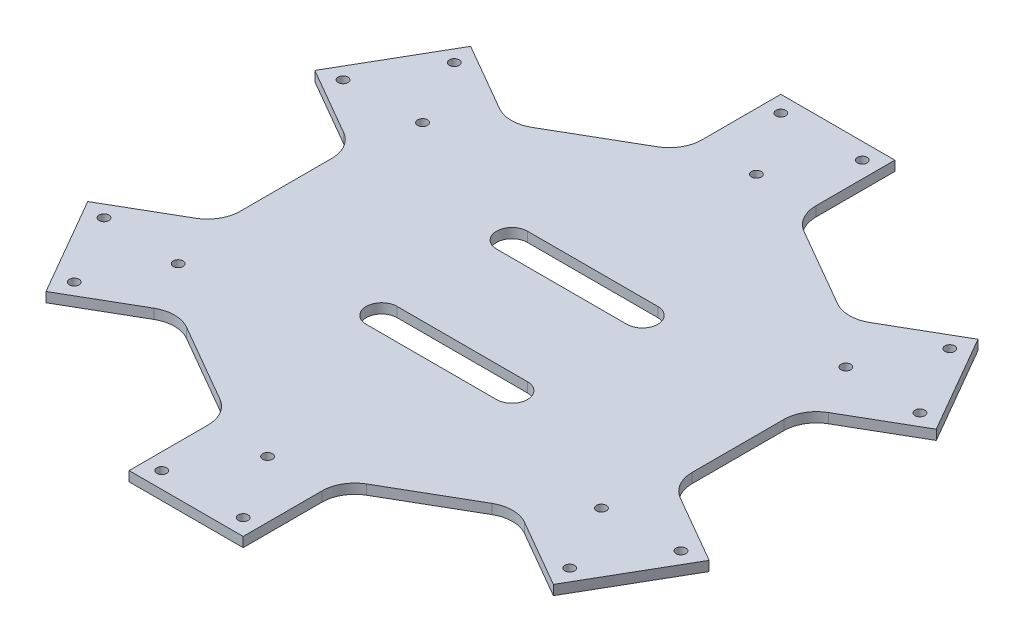
SolidWorks part; units mm, degrees
ref_plane "Ön Düzlem" through (0, 0, 0) normal (0, 0, 1) x (1, 0, 0)
ref_plane "Üst Düzlem" through (0, 0, 0) normal (0, 1, 0) x (1, 0, 0)
ref_plane "Sağ Düzlem" through (0, 0, 0) normal (1, 0, 0) x (0, 0, -1)
sketch "Çizim1" plane through (0, 0, 0) normal (0, 1, 0) x (1, 0, 0)
  line L0 (-17.5, 100) -> (17.5, 100)
  line L1 (95.3525, 34.8446) -> (77.8525, 65.1554)
  line L3 (-77.8525, 65.1554) -> (-95.3525, 34.8446)
  line L4 (-95.3525, -34.8446) -> (-77.8525, -65.1554)
  line L5 (-17.5, -100) -> (17.5, -100)
  line L6 (77.8525, -65.1554) -> (95.3525, -34.8446)
  line L7 (-17.5, 100) -> (-17.5, 75.7735)
  line L8 (17.5, 100) -> (17.5, 75.7735)
  line L9 (77.8525, 65.1554) -> (56.8718, 53.0422)
  line L11 (95.3525, 34.8446) -> (74.3718, 22.7313)
  line L12 (95.3525, -34.8446) -> (74.3718, -22.7313)
  line L14 (77.8525, -65.1554) -> (56.8718, -53.0422)
  line L15 (17.5, -100) -> (17.5, -75.7735)
  line L17 (-17.5, -100) -> (-17.5, -75.7735)
  line L18 (-77.8525, -65.1554) -> (-56.8718, -53.0422)
  line L20 (-95.3525, -34.8446) -> (-74.3718, -22.7313)
  line L21 (-95.3525, 34.8446) -> (-74.3718, 22.7313)
  line L23 (-77.8525, 65.1554) -> (-56.8718, 53.0422)
  line L24 (-46.8718, 53.0422) -> (-22.5, 67.1132)
  line L25 (22.5, 67.1132) -> (46.8718, 53.0422)
  line L26 (69.3718, 14.0711) -> (69.3718, -14.0711)
  line L27 (46.8718, -53.0422) -> (22.5, -67.1132)
  line L28 (-22.5, -67.1132) -> (-46.8718, -53.0422)
  line L29 (-69.3718, -14.0711) -> (-69.3718, 14.0711)
  line L39 (17.5, 100) -> (-17.5, 100) [skipped]
  line L40 (77.8525, 65.1554) -> (95.3525, 34.8446) [skipped]
  line L41 (-95.3525, 34.8446) -> (-77.8525, 65.1554) [skipped]
  line L42 (-77.8525, -65.1554) -> (-95.3525, -34.8446) [skipped]
  line L43 (17.5, -100) -> (-17.5, -100) [skipped]
  line L44 (95.3525, -34.8446) -> (77.8525, -65.1554) [skipped]
  arc A0 (-74.3718, 22.7313) -> (-69.3718, 14.0711) centre (-79.3718, 14.0711) cw
  arc A1 (-69.3718, -14.0711) -> (-74.3718, -22.7313) centre (-79.3718, -14.0711) cw
  arc A2 (-56.8718, -53.0422) -> (-46.8718, -53.0422) centre (-51.8718, -61.7024) cw
  arc A3 (-22.5, -67.1132) -> (-17.5, -75.7735) centre (-27.5, -75.7735) cw
  arc A4 (17.5, -75.7735) -> (22.5, -67.1132) centre (27.5, -75.7735) cw
  arc A5 (46.8718, -53.0422) -> (56.8718, -53.0422) centre (51.8718, -61.7024) cw
  arc A6 (74.3718, -22.7313) -> (69.3718, -14.0711) centre (79.3718, -14.0711) cw
  arc A7 (69.3718, 14.0711) -> (74.3718, 22.7313) centre (79.3718, 14.0711) cw
  arc A8 (46.8718, 53.0422) -> (56.8718, 53.0422) centre (51.8718, 61.7024) ccw
  arc A9 (22.5, 67.1132) -> (17.5, 75.7735) centre (27.5, 75.7735) cw
  arc A10 (-22.5, 67.1132) -> (-17.5, 75.7735) centre (-27.5, 75.7735) ccw
  arc A11 (-46.8718, 53.0422) -> (-56.8718, 53.0422) centre (-51.8718, 61.7024) cw
  circle A12 centre (-12.5, 95) radius 1.5
  circle A13 centre (12.5, 95) radius 1.5
  circle A14 centre (0, 75) radius 1.5
  circle A15 centre (64.9519, 37.5) radius 1.5
  circle A16 centre (88.5224, 36.6747) radius 1.5
  circle A17 centre (76.0224, 58.3253) radius 1.5
  circle A18 centre (64.9519, -37.5) radius 1.5
  circle A19 centre (76.0224, -58.3253) radius 1.5
  circle A20 centre (88.5224, -36.6747) radius 1.5
  circle A21 centre (0, -75) radius 1.5
  circle A22 centre (-12.5, -95) radius 1.5
  circle A23 centre (12.5, -95) radius 1.5
  circle A24 centre (-64.9519, -37.5) radius 1.5
  circle A25 centre (-88.5224, -36.6747) radius 1.5
  circle A26 centre (-76.0224, -58.3253) radius 1.5
  circle A27 centre (-64.9519, 37.5) radius 1.5
  circle A28 centre (-76.0224, 58.3253) radius 1.5
  circle A29 centre (-88.5224, 36.6747) radius 1.5
  point P12 (0, 100)
  point P37 (0, 0)
  point P95 (0, 0)
  dimension "D2" = 10
  dimension "D3" = 6
  dimension "D1" = 6
extrude "Yükseklik-Ekstrüzyon1" add sketch "Çizim1" along normal blind 3
sketch "Çizim3" plane through (0, 3, 0) normal (0, 1, 0) x (1, 0, 0)
  line L0 (0, 20) -> (0, -20)
  line L1 (-20, 20) -> (20, 20) construction
  line L2 (-20, -20) -> (20, -20) construction
  line L3 (-20, 24.75) -> (20, 24.75)
  line L4 (-20, 15.25) -> (20, 15.25)
  line L5 (-20, -15.25) -> (20, -15.25)
  line L6 (-20, -24.75) -> (20, -24.75)
  arc A0 (-20, 24.75) -> (-20, 15.25) centre (-20, 20) ccw
  arc A1 (20, 15.25) -> (20, 24.75) centre (20, 20) ccw
  arc A2 (-20, -15.25) -> (-20, -24.75) centre (-20, -20) ccw
  arc A3 (20, -24.75) -> (20, -15.25) centre (20, -20) ccw
  point P4 (0, 0)
  point P8 (0, 20)
  point P13 (0, -20)
extrude "Kes-Ekstrüzyon1" cut sketch "Çizim3" against normal blind 3 contours L4 A1 L3 A0 | L5 A3 L6 A2
